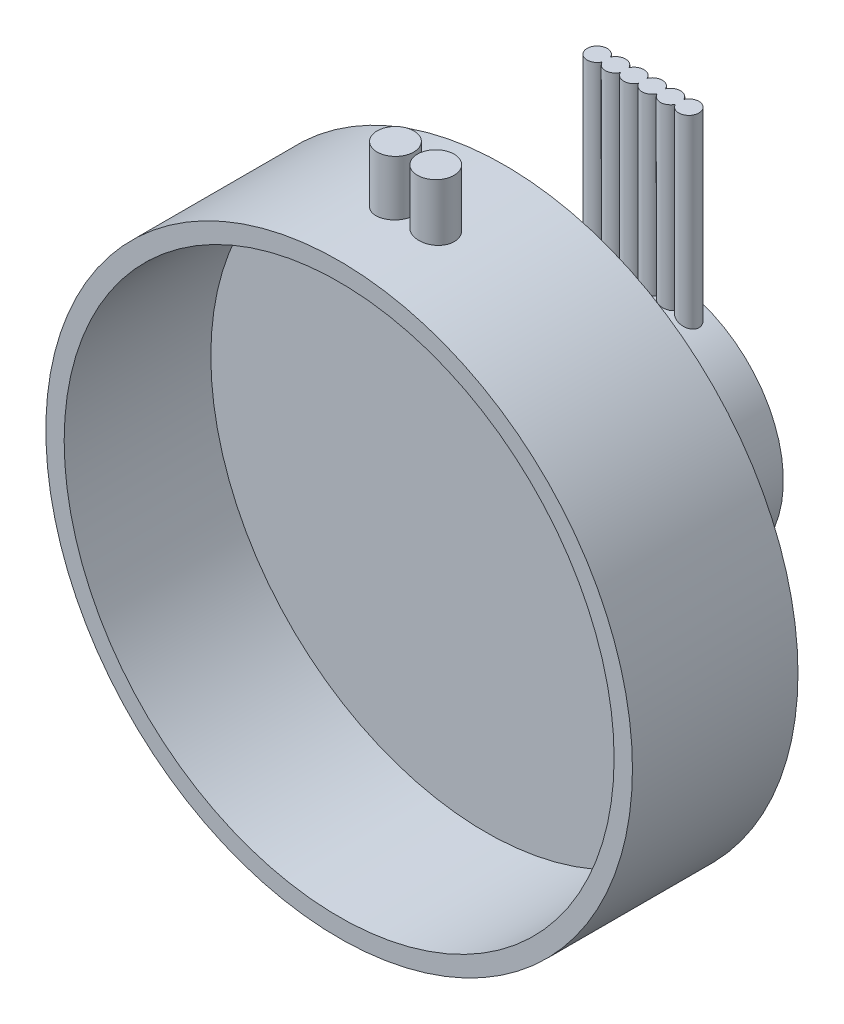
SolidWorks part; units mm, degrees
ref_plane "Plan de face" through (0, 0, 0) normal (0, 0, 1) x (1, 0, 0)
ref_plane "Plan de dessus" through (0, 0, 0) normal (0, 1, 0) x (1, 0, 0)
ref_plane "Plan de droite" through (0, 0, 0) normal (1, 0, 0) x (0, 0, -1)
sketch "Esquisse1" plane through (0, 0, 0) normal (0, 0, 1) x (1, 0, 0)
  circle A0 centre (0, 0) radius 16
  dimension "D1" = 32
extrude "Boss.-Extru.1" add sketch "Esquisse1" along normal blind 9.03
sketch "Esquisse2" plane through (0, 0, 9.03) normal (0, 0, 1) x (1, 0, 0)
  circle A0 centre (0, 0) radius 15
extrude "Enlèv. mat.-Extru.1" cut sketch "Esquisse2" against normal blind 8
sketch "Esquisse3" plane through (0, 0, 0) normal (0, 0, -1) x (-1, 0, 0)
  circle A0 centre (0, 0) radius 7.5
extrude "Boss.-Extru.2" add sketch "Esquisse3" along normal blind 5
sketch "Esquisse4" plane through (0, 0, -5) normal (0, 0, -1) x (-1, 0, 0)
  circle A0 centre (0, 0) radius 7
extrude "Boss.-Extru.3" add sketch "Esquisse4" along normal blind 1
sketch "Esquisse5" plane through (0, 0, -6) normal (0, 0, -1) x (-1, 0, 0)
  circle A0 centre (0, 0) radius 6.5
extrude "Boss.-Extru.4" add sketch "Esquisse5" along normal blind 2.7
ref_plane "Plan1" through (0, 16, 0) normal (0, 1, 0) x (-1, 0, 0)
sketch "Esquisse6" plane through (0, 16, 0) normal (0, 1, 0) x (-1, 0, 0)
  line L0 (1.1, 4.8577) -> (-1.1, 4.8577) construction
  line L1 (0, -13.7886) -> (0, 4.8577) construction
  circle A0 centre (1.1, 4.8577) radius 1
  circle A1 centre (-1.1, 4.8577) radius 1
  dimension "D1" = 2
  dimension "D2" = 2
  dimension "D3" = 2.2
extrude "Boss.-Extru.5" add sketch "Esquisse6" along normal blind 3 and the other way blind 0.5
sketch "Esquisse7" plane through (0, 16, 0) normal (0, 1, 0) x (-1, 0, 0)
  line L0 (2.7182, -7.7638) -> (-2.3246, -7.7638) construction
  arc A0 (2.2182, -7.9929) -> (2.2182, -7.5346) centre (2.7182, -7.7638) ccw
  arc A1 (2.2182, -7.5346) -> (1.2182, -7.5346) centre (1.7182, -7.7638) ccw
  arc A2 (1.2182, -7.5346) -> (0.2182, -7.5346) centre (0.7182, -7.7638) ccw
  arc A3 (0.2182, -7.5346) -> (-0.7818, -7.5346) centre (-0.2818, -7.7638) ccw
  arc A4 (-0.7818, -7.5346) -> (-1.7818, -7.5346) centre (-1.2818, -7.7638) ccw
  arc A5 (-1.7818, -7.5346) -> (-1.7818, -7.9929) centre (-2.2818, -7.7638) ccw
  arc A6 (1.2182, -7.9929) -> (2.2182, -7.9929) centre (1.7182, -7.7638) ccw
  arc A7 (0.2182, -7.9929) -> (1.2182, -7.9929) centre (0.7182, -7.7638) ccw
  arc A8 (-0.7818, -7.9929) -> (0.2182, -7.9929) centre (-0.2818, -7.7638) ccw
  arc A9 (-1.7818, -7.9929) -> (-0.7818, -7.9929) centre (-1.2818, -7.7638) ccw
  dimension "D1" = 1.1
  dimension "D2" = 6
extrude "Boss.-Extru.9" add sketch "Esquisse7" against normal blind 12
